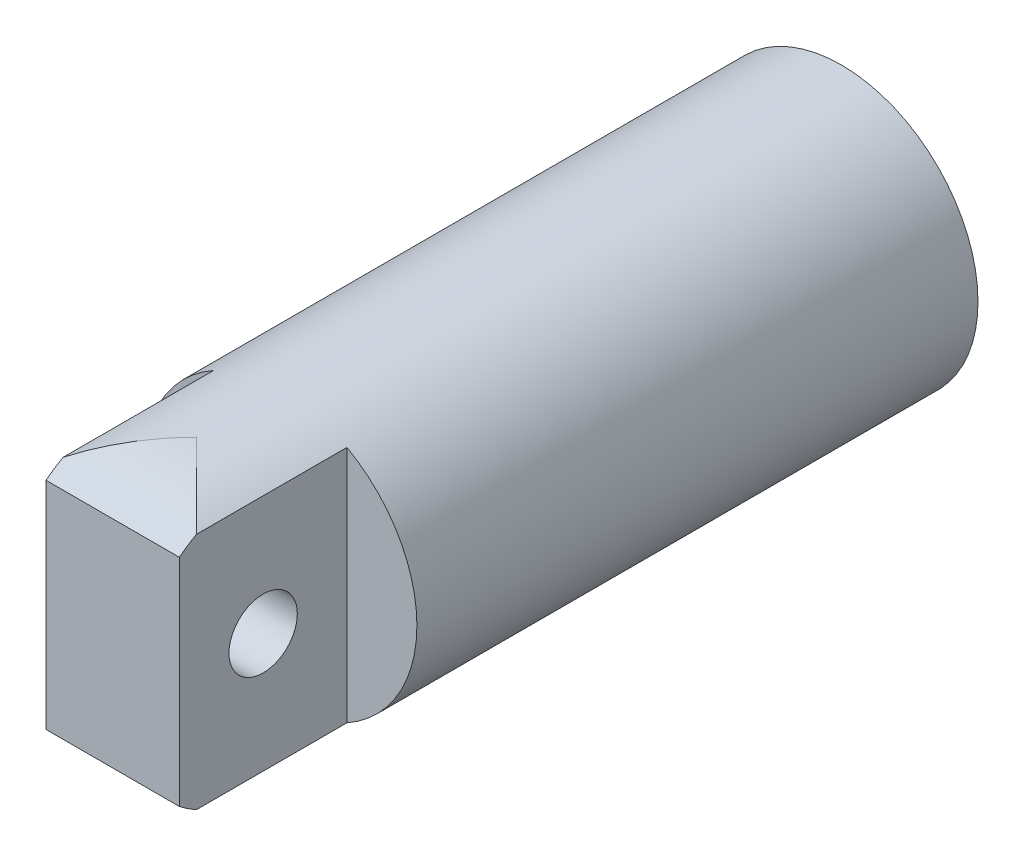
SolidWorks part; units mm, degrees
material "6061 Alloy"
ref_plane "Front" through (0, 0, 0) normal (0, 0, 1) x (1, 0, 0)
ref_plane "Top" through (0, 0, 0) normal (0, 1, 0) x (1, 0, 0)
ref_plane "Right" through (0, 0, 0) normal (1, 0, 0) x (0, 0, -1)
sketch "Sketch1" plane through (0, 0, 0) normal (0, 0, 1) x (1, 0, 0)
  circle A0 centre (0, 0) radius 4.7625
  dimension "D1" = 9.525
extrude "Boss-Extrude1" add sketch "Sketch1" along normal blind 25.4
sketch "Sketch2" plane through (0, 0, 25.4) normal (0, 0, 1) x (1, 0, 0)
  line L1 (-2.3241, 4.7625) -> (2.3241, 4.7625)
  line L2 (-2.3241, 4.7625) -> (-2.3241, -4.7625)
  line L3 (-2.3241, -4.7625) -> (2.3241, -4.7625)
  line L4 (2.3241, 4.7625) -> (2.3241, -4.7625)
  line L5 (-2.3241, 4.7625) -> (2.3241, -4.7625) construction
  line L6 (-2.3241, -4.7625) -> (2.3241, 4.7625) construction
  circle A0 centre (0, 0) radius 4.7625 construction
  point P0 (0, 0)
  dimension "D1" = 4.6482
extrude "Cut-Extrude1" cut sketch "Sketch2" against normal blind 5.842 flip side to cut
hole_wizard "3/32 (0.09375) Diameter Hole1" positions "Sketch3" profile "Sketch4" hole size "3/32" standard "ANSI Inch" end condition through all
sketch "Sketch3" plane through (-2.3241, 0, 0) normal (-1, 0, 0) x (0, 0, 1)
  line L0 (22.479, 4.1569) -> (22.479, -4.1569) construction
  line L1 (25.4, 4.1569) -> (19.558, 4.1569) construction
  line L2 (19.558, -4.1569) -> (25.4, -4.1569) construction
  line L3 (22.479, 0) -> (28.829, 0) construction
  circle A0 centre (22.479, 0) radius 2.9464 construction
  circle A1 centre (28.829, 0) radius 2.9464 construction
  point P9 (22.479, 0)
  dimension "D1" = 5.8928
  dimension "D2" = 6.35
sketch "Sketch4" plane through (-2.3241, 0, 22.479) normal (0, 1, 0) x (0, 0, 1)
  line L0 (0, 0) -> (0, 7.0866)
  line L1 (0, 7.0866) -> (1.1906, 7.0866)
  line L2 (1.1906, 7.0866) -> (1.1906, 0)
  line L5 (1.1906, 0) -> (0, 0)
  line L11 (0, -6.35) -> (0, 107.95) construction
  dimension "Thru Hole Dia." = 2.3812
  dimension "Thru Hole Depth" = 7.0866
sketch "Sketch5" plane through (-2.3241, 0, 0) normal (-1, 0, 0) x (0, 0, 1)
  line L0 (25.4, 4.7625) -> (0, 4.7625) construction
  line L1 (0, -4.7625) -> (25.4, -4.7625) construction
  line L2 (22.479, 4.7625) -> (32.004, 4.7625)
  line L3 (32.004, 4.7625) -> (32.004, -4.7625)
  line L4 (32.004, -4.7625) -> (22.479, -4.7625)
  arc A0 (22.479, 4.7625) -> (22.479, -4.7625) centre (22.479, 0) cw
  dimension "D1" = 9.525
extrude "Cut-Extrude2" cut sketch "Sketch5" against normal through all
hole_wizard "Tap Drill for #10-24 Tap1" positions "Sketch6" profile "Sketch8" hole size "#10-24" standard "ANSI Inch"
sketch "Sketch6" plane through (0, 0, 0) normal (0, 0, -1) x (-1, 0, 0)
  point P0 (0, 0)
sketch "Sketch8" plane through (0, 0, 0) normal (1, 0, 0) x (0, 1, 0)
  line L0 (0, 0) -> (0, 17.0158)
  line L1 (0, 17.0158) -> (1.8986, 15.875)
  line L2 (1.8986, 15.875) -> (1.8986, 0)
  line L5 (1.8986, 0) -> (0, 0)
  line L10 (0, 17.0158) -> (-1.8987, 15.875) construction
  line L11 (0, -6.35) -> (0, 107.95) construction
  dimension "Hole Dia." = 3.7973
  dimension "Hole Depth" = 15.875
  dimension "Drill Angle" = 118
